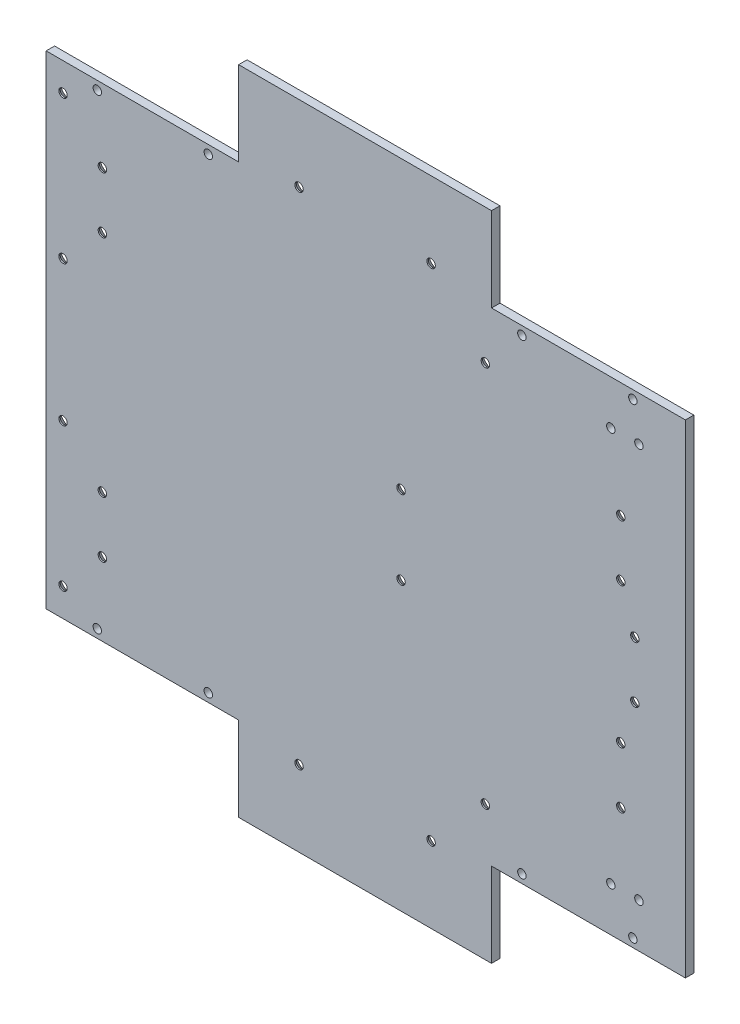
SolidWorks part; units mm, degrees
ref_plane "Front" through (0, 0, 0) normal (0, 0, 1) x (1, 0, 0)
ref_plane "Top" through (0, 0, 0) normal (0, 1, 0) x (1, 0, 0)
ref_plane "Right" through (0, 0, 0) normal (1, 0, 0) x (0, 0, -1)
sketch "草图1" plane through (0, 0, 0) normal (0, 0, 1) x (1, 0, 0)
  line L0 (-105.75, 86) -> (-105.75, 70)
  line L1 (-105.75, 86) -> (105.75, 86)
  line L2 (-105.75, 70) -> (-105.75, -86)
  line L3 (-105.75, -86) -> (105.75, -86)
  line L4 (105.75, 86) -> (105.75, -86)
  line L6 (-105.75, -86) -> (-75.75, -61.6028) construction
  line L7 (-129.21, 0) -> (-105.75, 0) construction
  line L43 (-58.101, -47.25) -> (-49.186, -40) construction
  line L48 (105.75, 0) -> (147.9998, 0) construction
  point P0 (0, 0)
extrude "凸台-拉伸1" add sketch "草图1" along normal blind 3
sketch "草图2" plane through (0, 0, 3) normal (0, 0, 1) x (1, 0, 0)
  line L0 (-171.9725, 0) -> (177.2997, 0) construction
  circle A0 centre (97.05, 83) radius 1.5
  circle A1 centre (-93.55, 83) radius 1.5
  circle A2 centre (57.55, 83) radius 1.5
  circle A3 centre (-54.05, 83) radius 1.5
  circle A4 centre (57.55, -83) radius 1.5
  circle A5 centre (97.05, -83) radius 1.5
  circle A6 centre (-54.05, -83) radius 1.5
  circle A7 centre (-93.55, -83) radius 1.5
extrude "切除-拉伸1" cut sketch "草图2" against normal blind 10
sketch "草图3" plane through (0, 0, 3) normal (0, 0, 1) x (1, 0, 0)
  line L0 (105.75, 86) -> (115.75, 86)
  line L1 (115.75, 86) -> (115.75, -86)
  line L2 (115.75, -86) -> (105.75, -86)
  line L3 (105.75, -86) -> (105.75, 86)
  line L4 (-43.25, 83) -> (46.75, 83)
  line L5 (-43.25, 83) -> (-43.25, 116)
  line L6 (-43.25, 116) -> (46.75, 116)
  line L7 (46.75, 116) -> (46.75, 83)
  line L8 (-153.596, 0) -> (171.6121, 0) construction
  line L9 (-43.25, -83) -> (46.75, -83)
  line L10 (46.75, -116) -> (46.75, -83)
  line L11 (-43.25, -83) -> (-43.25, -116)
  line L12 (-43.25, -116) -> (46.75, -116)
extrude "凸台-拉伸2" add sketch "草图3" against normal blind 3
sketch "草图4" plane through (0, 0, 3) normal (0, 0, 1) x (1, 0, 0)
  line L0 (-148.4712, 0) -> (147.7719, 0) construction
  circle A0 centre (44.55, 68) radius 1.5
  circle A1 centre (14.55, -14) radius 1.5
  circle A2 centre (14.55, 14) radius 1.5
  circle A3 centre (44.55, -68) radius 1.5
extrude "切除-拉伸2" cut sketch "草图4" against normal blind 10
sketch "草图5" plane through (0, 0, 3) normal (0, 0, 1) x (1, 0, 0)
  circle A3 centre (92.75, 45) radius 1.5
  circle A4 centre (92.75, 25) radius 1.5
  circle A5 centre (92.75, -25) radius 1.5
  circle A6 centre (92.75, -45) radius 1.5
extrude "切除-拉伸3" cut sketch "草图5" against normal blind 10
sketch "草图6" plane through (0, 0, 3) normal (0, 0, 1) x (1, 0, 0)
  line L0 (-159.5225, 0) -> (158.0171, 0) construction
  circle A0 centre (25.25, -89) radius 1.5
  circle A1 centre (-21.75, 89) radius 1.5
  circle A2 centre (25.25, 89) radius 1.5
  circle A3 centre (-21.75, -89) radius 1.5
extrude "切除-拉伸4" cut sketch "草图6" against normal blind 10
sketch "草图7" plane through (0, 0, 0) normal (0, 0, -1) x (-1, 0, 0)
  circle A3 centre (91.75, -60) radius 1.5
  circle A4 centre (91.75, -40) radius 1.5
  circle A5 centre (91.75, 60) radius 1.5
  circle A6 centre (91.75, 40) radius 1.5
extrude "切除-拉伸5" cut sketch "草图7" against normal blind 74
sketch "草图8" plane through (0, 0, 0) normal (0, 0, -1) x (-1, 0, 0)
  circle A1 centre (-97.75, 10) radius 1.5
  circle A2 centre (-97.75, -10) radius 1.5
extrude "切除-拉伸6" cut sketch "草图8" against normal blind 10
sketch "草图9" plane through (0, 0, 0) normal (0, 0, -1) x (-1, 0, 0)
  line L0 (105.75, 86) -> (111.75, 86)
  line L1 (111.75, 86) -> (111.75, -86)
  line L2 (111.75, -86) -> (105.75, -86)
  line L3 (105.75, -86) -> (105.75, 86)
extrude "凸台-拉伸3" add sketch "草图9" against normal blind 3
sketch "草图10" plane through (0, 0, 0) normal (0, 0, -1) x (-1, 0, 0)
  circle A2 centre (105.75, 76) radius 1.5
  circle A3 centre (105.75, 25) radius 1.5
  circle A4 centre (105.75, -25) radius 1.5
  circle A5 centre (105.75, -76) radius 1.5
extrude "切除-拉伸7" cut sketch "草图10" against normal blind 15
chamfer "倒角2" distance 2.5 angle 45 1 edges at (26.75, 89, 0)
chamfer "倒角3" distance 2.5 angle 45 9 edges at (-107.25, -76, 0) (-93.25, -60, 0) (-93.25, -40, 0) (-107.25, -25, 0) (-107.25, 25, 0) (-93.25, 40, 0) (-93.25, 60, 0) (-107.25, 76, 0) (-20.25, 89, 0)
chamfer "倒角4" distance 2.5 angle 45 3 edges at (46.05, -68, 0) (26.75, -89, 0) (-20.25, -89, 0)
chamfer "倒角5" distance 2.5 angle 45 6 edges at (94.25, 25, 0) (94.25, 45, 0) (96.25, 10, 0) (96.25, -10, 0) (94.25, -25, 0) (94.25, -45, 0)
chamfer "倒角6" distance 2.5 angle 45 1 edges at (16.05, 14, 0)
chamfer "倒角7" distance 2.5 angle 45 1 edges at (46.05, 68, 0)
chamfer "倒角8" distance 2.5 angle 45 1 edges at (16.05, -14, 0)
sketch "草图11" plane through (0, 0, 0) normal (0, 0, -1) x (-1, 0, 0)
  circle A0 centre (-89.2092, 70.25) radius 1.5
  circle A1 centre (-99.2092, 70.25) radius 1.5
extrude "切除-拉伸8" cut sketch "草图11" against normal blind 10
mirror "镜向1" about plane through (0, 0, 0) normal (0, 1, 0) of "切除-拉伸8"
